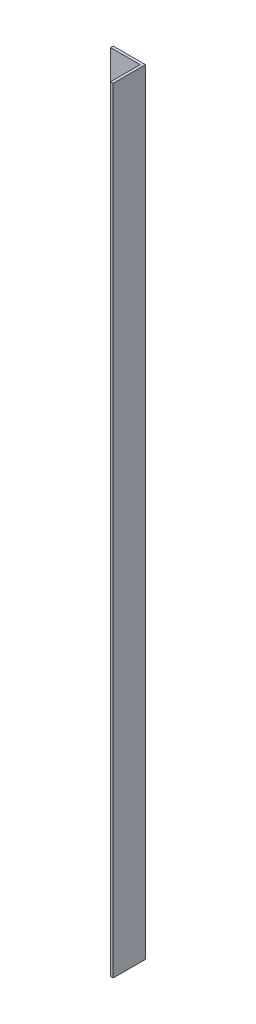
SolidWorks part; units mm, degrees
ref_plane "Front Plane" through (0, 0, 0) normal (0, 0, 1) x (1, 0, 0)
ref_plane "Top Plane" through (0, 0, 0) normal (0, 1, 0) x (1, 0, 0)
ref_plane "Right Plane" through (0, 0, 0) normal (1, 0, 0) x (0, 0, -1)
sketch "Sketch1" plane through (0, 0, 0) normal (0, 1, 0) x (1, 0, 0)
  line L0 (0, 0) -> (0, 19.05)
  line L1 (0, 19.05) -> (-19.05, 19.05)
  dimension "D1" = 19.05
  dimension "D2" = 19.05
extrude "Extrude-Thin1" add sketch "Sketch1" along normal blind 457.2 thin thin type one direction reverse wall 1.5875
